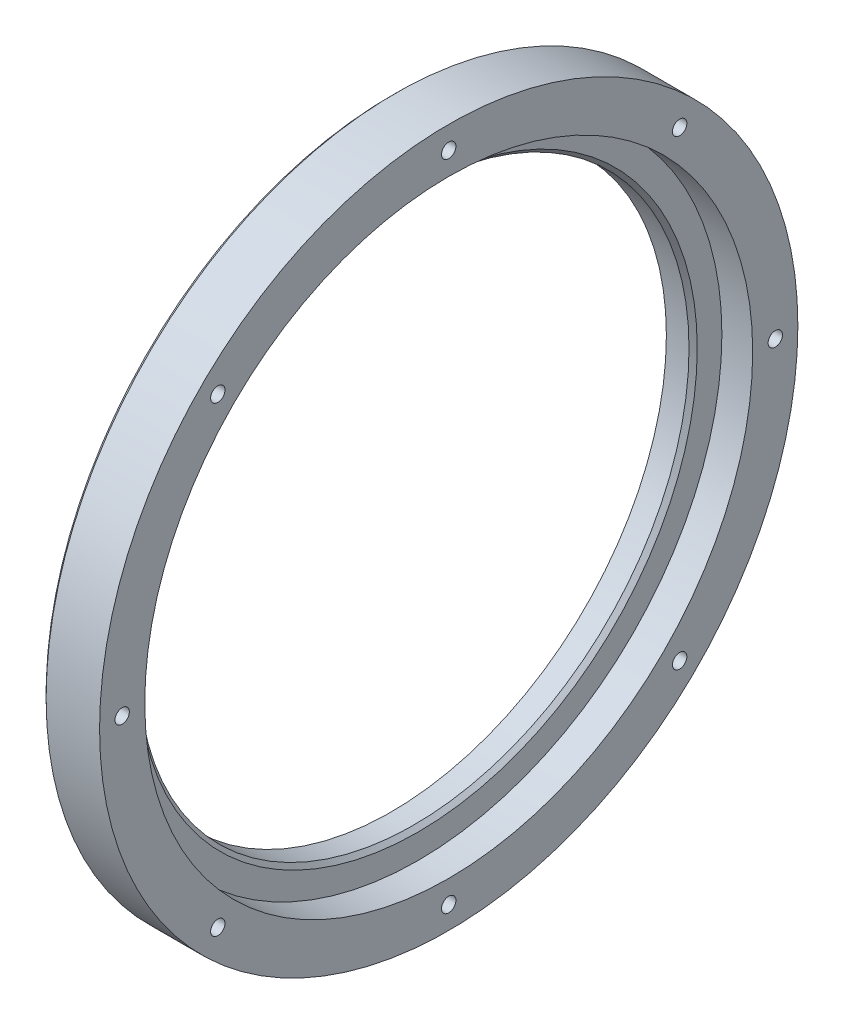
SolidWorks part; units mm, degrees
ref_plane "Płaszczyzna przednia" through (0, 0, 0) normal (0, 0, 1) x (1, 0, 0)
ref_plane "Płaszczyzna górna" through (0, 0, 0) normal (0, 1, 0) x (1, 0, 0)
ref_plane "Płaszczyzna prawa" through (0, 0, 0) normal (1, 0, 0) x (0, 0, -1)
sketch "Szkic1" plane through (0, 0, 0) normal (0, 0, 1) x (1, 0, 0)
  line L0 (-272.858, 75.0093) -> (-280.358, 75.0093)
  line L1 (-272.858, -79.75) -> (-272.858, 79.75) construction
  line L2 (-272.858, 86.0093) -> (-272.858, -83.9907) construction
  line L3 (-280.358, 75.0093) -> (-280.358, 68.0093)
  line L4 (-280.358, 68.0093) -> (-286.8712, 68.0093)
  line L5 (-286.8712, 68.0093) -> (-286.8712, 85.0093)
  line L6 (-285.8712, 86.0093) -> (-272.858, 86.0093)
  line L7 (-262.4033, 86.0093) -> (-272.858, 86.0093) construction
  line L8 (-268.908, 1.0093) -> (-389.244, 1.0093) construction
  line L10 (-286.8712, 85.0093) -> (-285.8712, 86.0093)
  line L11 (-279.858, -79.2) -> (-279.858, 79.2) construction
  line L12 (-272.858, 75.0093) -> (-272.858, 86.0093)
  line L13 (-268.908, -49.9907) -> (-268.908, 52.0093) construction
  point P4 (-286.8712, 86.0093)
  dimension "D1" = 1.5
  dimension "D2" = 18
  dimension "D3" = 0.5
revolve "Obrót1" add sketch "Szkic1" angle 360 about L8
sketch "Szkic2" plane through (-286.8712, 0, 0) normal (-1, 0, 0) x (0, 0, 1)
  line L0 (0, 1.0093) -> (67, 1.0093) construction
  line L1 (74, 1.0093) -> (85, 1.0093) construction
  line L2 (0, 1.0093) -> (47.3762, -46.3669) construction
  line L3 (52.3259, -51.3166) -> (60.1041, -59.0948) construction
  line L4 (0, 1.0093) -> (0, -65.9907) construction
  line L5 (0, -72.9907) -> (0, -83.9907) construction
  line L6 (0, 1.0093) -> (-47.3762, -46.3669) construction
  line L7 (-52.3259, -51.3166) -> (-60.1041, -59.0948) construction
  line L8 (0, 1.0093) -> (-67, 1.0093) construction
  line L9 (-74, 1.0093) -> (-85, 1.0093) construction
  line L10 (0, 1.0093) -> (-47.3762, 48.3854) construction
  line L11 (-52.3259, 53.3352) -> (-60.1041, 61.1133) construction
  line L12 (0, 1.0093) -> (0, 68.0093) construction
  line L13 (0, 75.0093) -> (0, 86.0093) construction
  line L14 (0, 1.0093) -> (47.3762, 48.3854) construction
  line L15 (52.3259, 53.3352) -> (60.1041, 61.1133) construction
  circle A0 centre (0, 1.0093) radius 85 construction
  circle A1 centre (79.5, 1.0093) radius 1.75
  circle A2 centre (59.9476, 1.0093) radius 1.75 construction
  circle A3 centre (0, 1.0093) radius 74 construction
  circle A4 centre (0, 1.0093) radius 67 construction
  circle A5 centre (56.215, -55.2057) radius 1.75
  circle A6 centre (0, -78.4907) radius 1.75
  circle A7 centre (-56.215, -55.2057) radius 1.75
  circle A8 centre (-79.5, 1.0093) radius 1.75
  circle A9 centre (-56.215, 57.2243) radius 1.75
  circle A10 centre (0, 80.5093) radius 1.75
  circle A11 centre (56.215, 57.2243) radius 1.75
  point P58 (0, 1.0093)
extrude "Wytnij-wyciągnięcie1" cut sketch "Szkic2" against normal through all
sketch "Szkic4" plane through (-286.8712, 0, 0) normal (-1, 0, 0) x (0, 0, 1)
  line L0 (0, 1.0093) -> (91.9385, 1.0093) construction
  line L1 (0, 1.0093) -> (65.0103, -64.0011) construction
  line L2 (0, 1.0093) -> (0, -90.9292) construction
  line L3 (0, 1.0093) -> (-65.0103, -64.0011) construction
  line L4 (0, 1.0093) -> (-91.9385, 1.0093) construction
  line L5 (0, 1.0093) -> (-65.0103, 66.0196) construction
  line L6 (0, 1.0093) -> (0, 92.9478) construction
  line L7 (0, 1.0093) -> (65.0103, 66.0196) construction
  circle A0 centre (79.5, 1.0093) radius 3
  circle A1 centre (59.9476, 1.0093) radius 3 construction
  circle A2 centre (56.215, -55.2057) radius 3
  circle A3 centre (0, -78.4907) radius 3
  circle A4 centre (-56.215, -55.2057) radius 3
  circle A5 centre (-79.5, 1.0093) radius 3
  circle A6 centre (-56.215, 57.2243) radius 3
  circle A7 centre (0, 80.5093) radius 3
  circle A8 centre (56.215, 57.2243) radius 3
  point P32 (0, 1.0093)
extrude "Wytnij-wyciągnięcie2" cut sketch "Szkic4" against normal blind 4
chamfer "Sfazowanie1" distance 1 angle 45 1 edges at (-280.358, 1.0093, -67)
move or copy body "Obiekt-Przenieś/Kopiuj1" [suppressed] bodies to move or copy 103 copy no rotation origin (-139.9323, 1.0093, 139.9323) rotation axis (0.7071, 0, 0.7071) rotation angle 180
